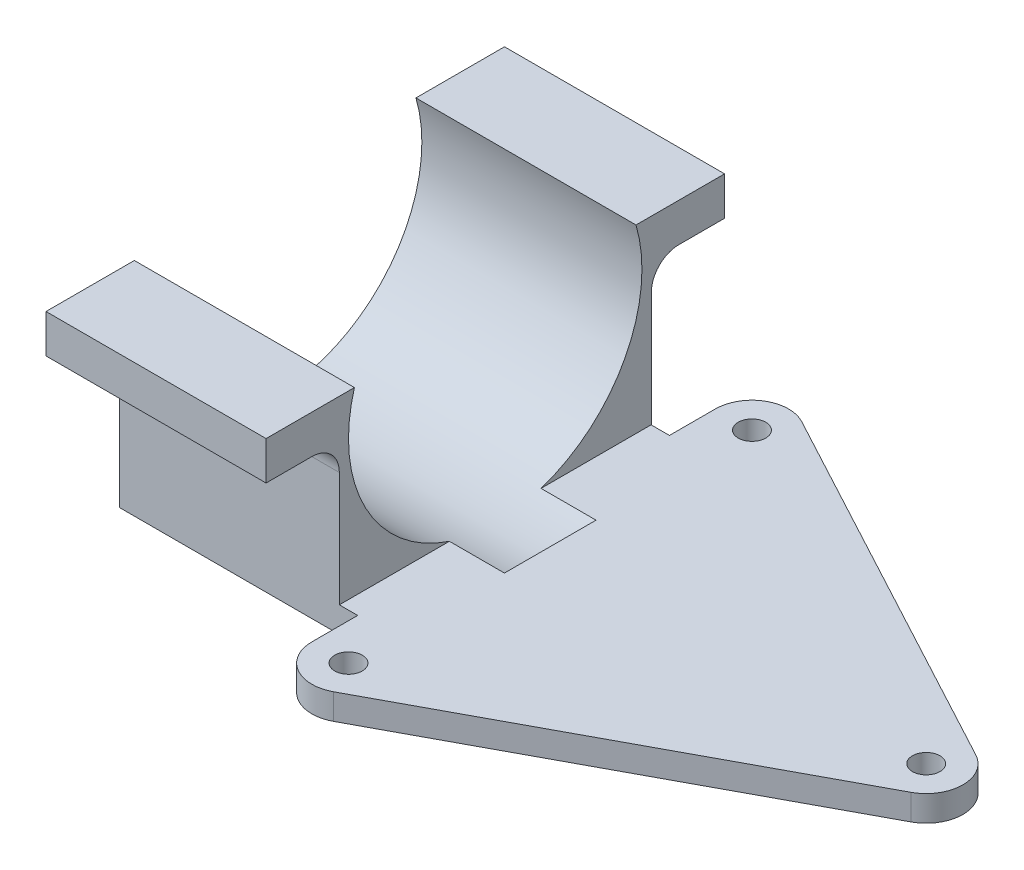
SolidWorks part; units mm, degrees
ref_plane "Спереди" through (0, 0, 0) normal (0, 0, 1) x (1, 0, 0)
ref_plane "Сверху" through (0, 0, 0) normal (0, 1, 0) x (1, 0, 0)
ref_plane "Справа" through (0, 0, 0) normal (1, 0, 0) x (0, 0, -1)
sketch "Эскиз1" plane through (0, 0, 0) normal (0, 1, 0) x (1, 0, 0)
  line L0 (0, 22) -> (0, 17)
  line L1 (0, 0) -> (65.5483, 0) construction
  line L2 (-26, 0) -> (-26, 17)
  line L3 (5.8913, -25.5246) -> (46.8913, -3.5246)
  line L4 (5.8913, 25.5246) -> (46.8913, 3.5246)
  line L5 (-26, 0) -> (-26, -17)
  line L6 (-26, 17) -> (0, 17)
  line L7 (-26, -17) -> (0, -17)
  line L8 (0, -17) -> (0, -22)
  arc A0 (5.8913, 25.5246) -> (0, 22) centre (4, 22) ccw
  arc A1 (5.8913, -25.5246) -> (0, -22) centre (4, -22) cw
  arc A2 (46.8913, -3.5246) -> (46.8913, 3.5246) centre (45, 0) ccw
  circle A3 centre (4, 22) radius 1.5
  circle A4 centre (4, -22) radius 1.5
  circle A5 centre (45, 0) radius 1.5
  dimension "D1" = 4
  dimension "D2" = 45
  dimension "D3" = 22
  dimension "D4" = 22
  dimension "D5" = 26
extrude "Вытянуть1" add sketch "Эскиз1" along normal blind 2.8
sketch "Эскиз2" plane through (0, 2.8, 0) normal (0, 1, 0) x (1, 0, 0)
  line L0 (-2, 27.4853) -> (-2, -25.2317) construction
  line L1 (0, 22) -> (0, 17) construction
  line L2 (-2, 17.0223) -> (-26, 17)
  line L3 (-26, 17) -> (-26, -17)
  line L4 (-26, -17) -> (-2, -17)
  line L5 (-26, -17) -> (0, -17) construction
  line L6 (-2, -17) -> (-2, 17.0223)
  dimension "D1" = 2
extrude "Вытянуть2" add sketch "Эскиз2" along normal blind 15.5
sketch "Эскиз3" plane through (0, 18.3, 0) normal (0, 1, 0) x (1, 0, 0)
  line L0 (-2, 0) -> (-33.6917, 0) construction
  line L3 (-2, -24.9888) -> (-2, 25.0112)
  line L6 (-2, 25.0112) -> (-26, 25.0112)
  line L7 (-26, 25.0112) -> (-26, -24.9888)
  line L8 (-26, -24.9888) -> (-2, -24.9888)
extrude "Вытянуть3" add sketch "Эскиз3" along normal blind 4.2
sketch "Эскиз4" plane through (-26, 0, 0) normal (-1, 0, 0) x (0, 0, 1)
  circle A0 centre (0, 18) radius 16
extrude "Вытянуть4" cut sketch "Эскиз4" against normal blind 30
fillet "Скругление1" radius 3 2 edges
